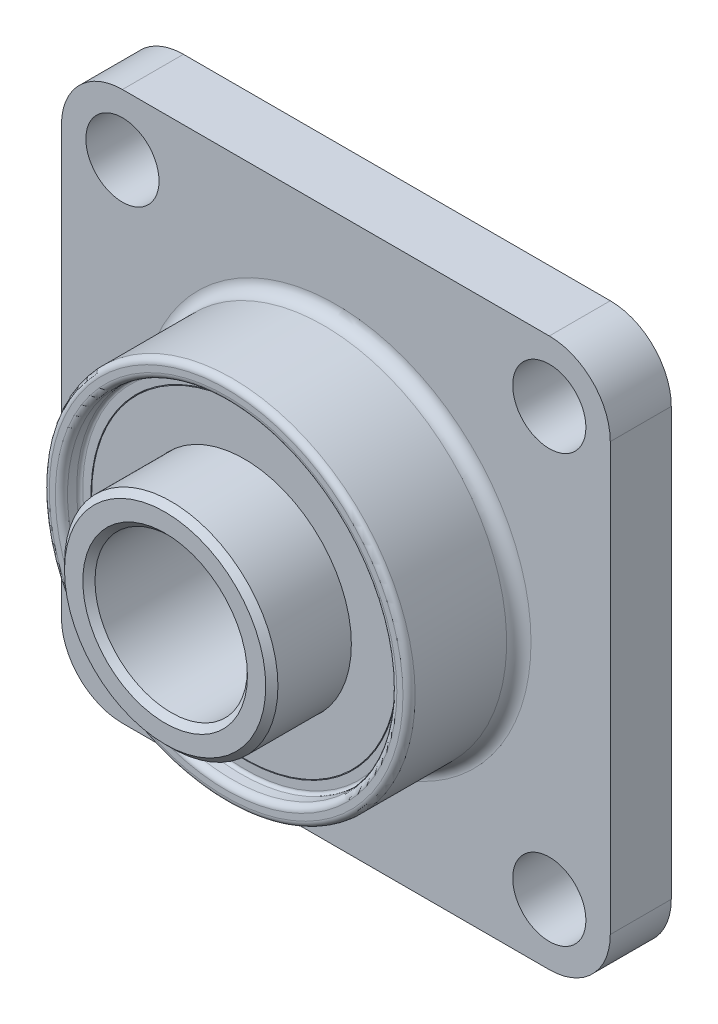
SolidWorks part; units mm, degrees
ref_plane "Front Plane" through (0, 0, 0) normal (0, 0, 1) x (1, 0, 0)
ref_plane "Top Plane" through (0, 0, 0) normal (0, 1, 0) x (1, 0, 0)
ref_plane "Right Plane" through (0, 0, 0) normal (1, 0, 0) x (0, 0, -1)
sketch "Sketch1" plane through (0, 0, 0) normal (0, 0, 1) x (1, 0, 0)
  line L1 (-35, -45) -> (35, -45)
  line L2 (-45, -35) -> (-45, 35)
  line L3 (-35, 45) -> (35, 45)
  line L4 (45, -35) -> (45, 35)
  line L5 (-45, -45) -> (45, 45) construction
  line L6 (-45, 45) -> (45, -45) construction
  arc A0 (35, 45) -> (45, 35) centre (35, 35) cw
  arc A1 (35, -45) -> (45, -35) centre (35, -35) ccw
  arc A2 (-35, -45) -> (-45, -35) centre (-35, -35) cw
  arc A3 (-45, 35) -> (-35, 45) centre (-35, 35) cw
  circle A4 centre (-35, 35) radius 6
  circle A5 centre (35, 35) radius 6
  circle A6 centre (35, -35) radius 6
  circle A7 centre (-35, -35) radius 6
  circle A8 centre (0, 0) radius 24
  point P0 (0, 0)
  dimension "D3" = 10
  dimension "D1" = 90
  dimension "D2" = 90
extrude "Boss-Extrude1" add sketch "Sketch1" along normal blind 10
sketch "Sketch2" plane through (0, 0, 10) normal (0, 0, 1) x (1, 0, 0)
  circle A0 centre (0, 0) radius 30
  circle A1 centre (0, 0) radius 27
  dimension "D1" = 3
extrude "Boss-Extrude2" add sketch "Sketch2" along normal blind 18
fillet "Fillet1" radius 2 1 edges at (-30, 0, 10)
sketch "Sketch3" plane through (0, 0, 10) normal (0, 0, 1) x (1, 0, 0)
  circle A0 centre (0, 0) radius 27.1543
  circle A1 centre (0, 0) radius 25.1543
  dimension "D1" = 2
extrude "Boss-Extrude3" add sketch "Sketch3" along normal blind 15
fillet "Fillet2" radius 1 2 edges at (27, 0, 28) (30, 0, 28)
sketch "Sketch4" plane through (0, 0, 10) normal (0, 0, 1) x (1, 0, 0)
  circle A0 centre (0, 0) radius 25.0418
  circle A1 centre (0, 0) radius 23.5418
  dimension "D1" = 1.5
extrude "Boss-Extrude4" add sketch "Sketch4" along normal blind 15
fillet "Fillet3" radius 0.5 1 edges at (27, 0, 25)
sketch "Sketch5" plane through (0, 0, 10) normal (0, 0, 1) x (1, 0, 0)
  circle A0 centre (0, 0) radius 23.5418
  circle A1 centre (0, 0) radius 17.5418
  dimension "D1" = 6
extrude "Boss-Extrude5" add sketch "Sketch5" along normal blind 15
sketch "Sketch6" plane through (0, 0, 10) normal (0, 0, 1) x (1, 0, 0)
  circle A0 centre (0, 0) radius 17.5
  circle A1 centre (0, 0) radius 12.5
  dimension "D1" = 5
extrude "Boss-Extrude6" add sketch "Sketch6" along normal blind 28
sketch "Sketch8" plane through (0, 0, 0) normal (0, 0, -1) x (-1, 0, 0)
  line L4 (23.6863, -39) -> (-23.6863, -39)
  line L5 (-39, -23.6863) -> (-39, 23.6863)
  line L9 (-23.6863, 39) -> (23.6863, 39)
  line L10 (39, 23.6863) -> (39, -23.6863)
  arc A12 (-39, 23.6863) -> (-23.6863, 39) centre (-35, 35) ccw
  arc A13 (-23.6863, -39) -> (-39, -23.6863) centre (-35, -35) ccw
  arc A14 (39, -23.6863) -> (23.6863, -39) centre (35, -35) ccw
  arc A15 (23.6863, 39) -> (39, 23.6863) centre (35, 35) ccw
extrude "Cut-Extrude2" cut sketch "Sketch8" against normal blind 6
sketch "Sketch9" plane through (0, 0, 10) normal (0, 0, -1) x (-1, 0, 0)
  circle A0 centre (0, 0) radius 12.5
  circle A1 centre (0, 0) radius 17.5
extrude "Boss-Extrude7" add sketch "Sketch9" along normal blind 10
chamfer "Chamfer1" distance 1 angle 45 2 edges at (12.5, 0, 38) (17.5, 0, 38)
chamfer "Chamfer2" distance 1 angle 45 2 edges at (-12.5, 0, 0) (-17.5, 0, 0)
